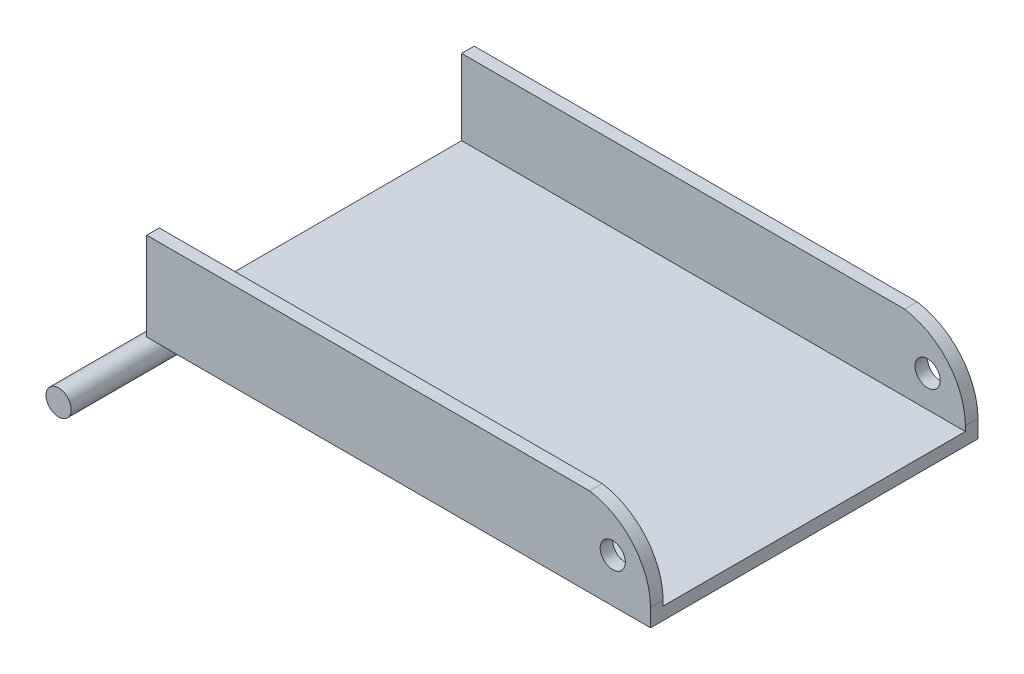
SolidWorks part; units mm, degrees
other "DetailItem3"
other "Weld Folder"
other "Weld Bead3"
ref_plane "Front Plane" through (0, 0, 0) normal (0, 0, 1) x (1, 0, 0)
ref_plane "Top Plane" through (0, 0, 0) normal (0, 1, 0) x (1, 0, 0)
ref_plane "Right Plane" through (0, 0, 0) normal (1, 0, 0) x (0, 0, -1)
sketch "Sketch1" plane through (0, 0, 0) normal (0, 0, 1) x (1, 0, 0)
  circle A0 centre (0, 0) radius 5
  dimension "D1" = 10
extrude "Boss-Extrude1" add sketch "Sketch1" along normal blind 200
sketch "Sketch2" plane through (0, 0, 0) normal (1, 0, 0) x (0, 0, -1)
  line L0 (0, 5) -> (-200, 5) construction
  line L1 (-165, 5) -> (-35, 5)
  line L2 (-165, 5) -> (-165, 10)
  line L3 (-165, 10) -> (-35, 10)
  line L4 (-35, 5) -> (-35, 10)
  line L5 (-200, 5) -> (-200, -5) construction
  point P6 (-100, 10)
  dimension "D1" = 5
  dimension "D2" = 100
  dimension "D3" = 35
  dimension "D4" = 130
extrude "Boss-Extrude2" add sketch "Sketch2" along normal blind 200 separate body
sketch "Sketch3" plane through (0, 10, 0) normal (0, 1, 0) x (1, 0, 0)
  line L0 (200, -35) -> (200, -165) construction
  line L1 (0, -35) -> (200, -35)
  line L2 (0, -35) -> (0, -40)
  line L3 (0, -40) -> (200, -40)
  line L4 (200, -35) -> (200, -40)
  line L5 (200, -165) -> (0, -165) construction
  line L6 (0, -165) -> (200, -165)
  line L7 (0, -165) -> (0, -160)
  line L8 (0, -160) -> (200, -160)
  line L9 (200, -165) -> (200, -160)
  dimension "D1" = 5
  dimension "D2" = 5
extrude "Boss-Extrude3" add sketch "Sketch3" along normal blind 30
sketch "Sketch4" plane through (0, 0, 165) normal (0, 0, 1) x (1, 0, 0)
  line L0 (200, 40) -> (200, 5) construction
  line L1 (200, 5) -> (0, 5) construction
  circle A0 centre (185, 22.5) radius 5
  dimension "D1" = 10
  dimension "D2" = 15
  dimension "D3" = 17.5
extrude "Cut-Extrude1" cut sketch "Sketch4" against normal through all
sketch "Sketch5" plane through (0, 0, 165) normal (0, 0, 1) x (1, 0, 0)
  line L0 (0, 40) -> (200, 40) construction
  line L1 (200, 40) -> (200, 5) construction
  line L2 (175.8328, 40) -> (193.1657, 65.0109)
  line L3 (193.1657, 65.0109) -> (236.6343, 44.8515)
  line L4 (236.6343, 44.8515) -> (213.8577, 11.9855)
  line L5 (213.8577, 11.9855) -> (200, 11.9855)
  arc A0 (175.8328, 40) -> (200, 11.9855) centre (171.3951, 11.7404) cw
  point P7 (175.8731, 40)
  point P11 (200, 11.9855)
extrude "Cut-Extrude2" cut sketch "Sketch5" against normal through all
